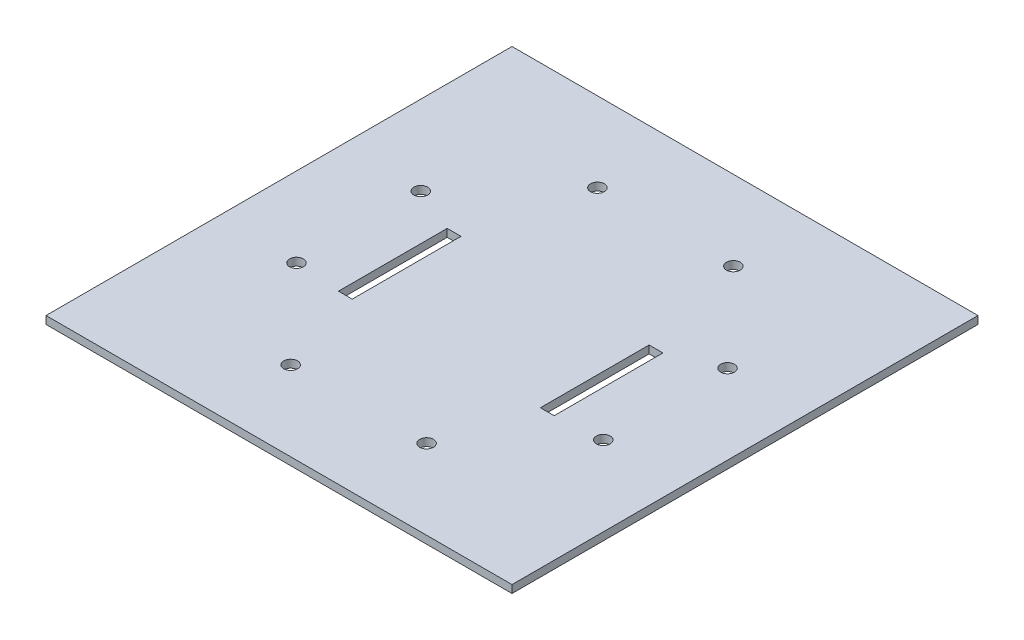
SolidWorks part; units mm, degrees
ref_plane "Front Plane" through (0, 0, 0) normal (0, 0, 1) x (1, 0, 0)
ref_plane "Top Plane" through (0, 0, 0) normal (0, 1, 0) x (1, 0, 0)
ref_plane "Right Plane" through (0, 0, 0) normal (1, 0, 0) x (0, 0, -1)
sketch "Sketch1" plane through (0, 0, 0) normal (0, 1, 0) x (1, 0, 0)
  line L1 (44.88, 74.7331) -> (164.88, 74.7331)
  line L2 (44.88, 74.7331) -> (44.88, -45.2669)
  line L3 (44.88, -45.2669) -> (164.88, -45.2669)
  line L4 (164.88, 74.7331) -> (164.88, -45.2669)
  dimension "D1" = 120
extrude "Boss-Extrude1" add sketch "Sketch1" along normal blind 2
sketch "Sketch2" plane through (0, 2, 0) normal (0, 1, 0) x (1, 0, 0)
  line L0 (65.38, 30.7331) -> (44.88, 30.7331) construction
  line L1 (65.38, -1.2669) -> (65.38, 30.7331) construction
  line L2 (65.38, 30.7331) -> (144.38, 30.7331) construction
  line L3 (144.38, 30.7331) -> (144.38, -1.2669) construction
  line L4 (144.38, -1.2669) -> (65.38, -1.2669) construction
  line L5 (44.88, 74.7331) -> (44.88, -45.2669) construction
  line L6 (144.38, 30.7331) -> (164.88, 30.7331) construction
  line L7 (164.88, -45.2669) -> (164.88, 74.7331) construction
  line L8 (74.6459, -45.2669) -> (74.6459, -1.2669) construction
  line L9 (44.88, -45.2669) -> (164.88, -45.2669) construction
  line L10 (119.5099, 30.7331) -> (119.5099, 74.7331) construction
  line L11 (164.88, 74.7331) -> (44.88, 74.7331) construction
  circle A0 centre (65.38, 30.7331) radius 1.775
  circle A1 centre (65.38, -1.2669) radius 1.775
  circle A2 centre (144.38, -1.2669) radius 1.775
  circle A3 centre (144.38, 30.7331) radius 1.775
  dimension "D3" = 3.55
  dimension "D1" = 32
  dimension "D2" = 79
extrude "Cut-Extrude1" cut sketch "Sketch2" against normal through all
sketch "Sketch3" plane through (0, 2, 0) normal (0, 1, 0) x (1, 0, 0)
  line L0 (87.38, -24.7669) -> (87.38, 54.2331) construction
  line L1 (87.38, 54.2331) -> (122.38, 54.2331) construction
  line L2 (122.38, 54.2331) -> (122.38, -24.7669) construction
  line L3 (122.38, -24.7669) -> (87.38, -24.7669) construction
  line L4 (104.88, -45.2669) -> (104.88, -24.7669) construction
  line L6 (44.88, -45.2669) -> (164.88, -45.2669) construction
  line L7 (44.88, 14.7331) -> (87.38, 14.7331) construction
  line L8 (44.88, 74.7331) -> (44.88, -45.2669) construction
  line L9 (104.88, 54.2331) -> (104.88, 74.7331) construction
  line L10 (164.88, 74.7331) -> (44.88, 74.7331) construction
  line L11 (122.38, 14.7331) -> (164.88, 14.7331) construction
  line L12 (164.88, -45.2669) -> (164.88, 74.7331) construction
  circle A0 centre (87.38, -24.7669) radius 1.775
  circle A1 centre (87.38, 54.2331) radius 1.775
  circle A2 centre (122.38, -24.7669) radius 1.775
  circle A3 centre (122.38, 54.2331) radius 1.775
  dimension "D3" = 3.55
  dimension "D1" = 35
  dimension "D2" = 79
extrude "Cut-Extrude2" cut sketch "Sketch3" against normal through all
sketch "Sketch4" plane through (0, 2, 0) normal (0, 1, 0) x (1, 0, 0)
  line L0 (78.88, 9.6861) -> (130.88, 9.6861) construction
  line L1 (130.88, 9.6861) -> (130.88, 19.7802) construction
  line L2 (130.88, 19.7802) -> (78.88, 19.7802) construction
  line L3 (78.88, 19.7802) -> (78.88, 9.6861) construction
  line L4 (104.88, -45.2669) -> (104.88, 9.6861) construction
  line L5 (44.88, -45.2669) -> (164.88, -45.2669) construction
  line L6 (130.88, 14.7331) -> (164.88, 14.7331) construction
  line L7 (164.88, -45.2669) -> (164.88, 74.7331) construction
  line L8 (44.88, 14.7331) -> (78.88, 14.7331) construction
  line L9 (44.88, 74.7331) -> (44.88, -45.2669) construction
  line L10 (104.88, 19.7802) -> (104.88, 74.7331) construction
  line L11 (164.88, 74.7331) -> (44.88, 74.7331) construction
  line L12 (78.88, -2.1796) -> (78.88, 25.8204) construction
  line L13 (80.655, -2.1796) -> (77.105, -2.1796)
  line L14 (80.655, -2.1796) -> (80.655, 25.8204)
  line L15 (80.655, 25.8204) -> (77.105, 25.8204)
  line L16 (77.105, -2.1796) -> (77.105, 25.8204)
  line L17 (129.105, -2.1796) -> (132.655, -2.1796)
  line L18 (129.105, -2.1796) -> (129.105, 25.8204)
  line L19 (129.105, 25.8204) -> (132.655, 25.8204)
  line L20 (132.655, -2.1796) -> (132.655, 25.8204)
  line L21 (130.88, -2.1796) -> (130.88, 25.8204) construction
  dimension "D1" = 52
  dimension "D2" = 3.55
  dimension "D3" = 28
extrude "Cut-Extrude3" cut sketch "Sketch4" against normal through all
